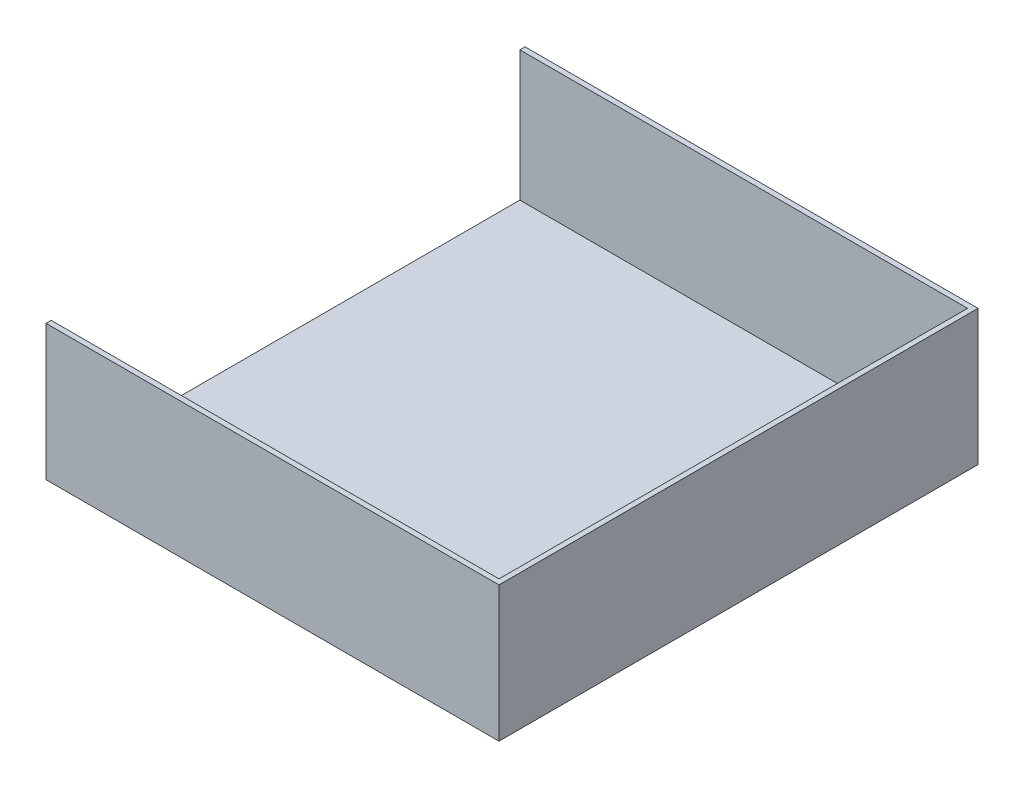
SolidWorks part; units mm, degrees
ref_plane "Front Plane" through (0, 0, 0) normal (0, 0, 1) x (1, 0, 0)
ref_plane "Top Plane" through (0, 0, 0) normal (0, 1, 0) x (1, 0, 0)
ref_plane "Right Plane" through (0, 0, 0) normal (1, 0, 0) x (0, 0, -1)
sketch "Sketch1" plane through (0, 0, 0) normal (0, 1, 0) x (1, 0, 0)
  line L1 (0, 0) -> (279.4, 0)
  line L2 (0, 0) -> (0, 292.1)
  line L3 (0, 292.1) -> (279.4, 292.1)
  line L4 (279.4, 0) -> (279.4, 292.1)
  dimension "D1" = 279.4
  dimension "D2" = 292.1
extrude "Boss-Extrude1" add sketch "Sketch1" along normal blind 82.55
sketch "Sketch3" plane through (0, 82.55, 0) normal (0, 1, 0) x (1, 0, 0)
  line L14 (3.175, 3.175) -> (276.225, 3.175)
  line L15 (276.225, 3.175) -> (276.225, 288.925)
  line L16 (3.175, 288.925) -> (3.175, 3.175)
  line L17 (276.225, 288.925) -> (3.175, 288.925)
  line L18 (3.175, 3.175) -> (276.225, 3.175)
  line L19 (276.225, 3.175) -> (276.225, 288.925)
  line L20 (3.175, 288.925) -> (3.175, 3.175)
  line L21 (276.225, 288.925) -> (3.175, 288.925)
  dimension "D1" = 3.175
extrude "Cut-Extrude1" cut sketch "Sketch3" against normal blind 79.375
sketch "Sketch4" plane through (0, 82.55, 0) normal (0, 1, 0) x (1, 0, 0)
  line L0 (279.4, 292.1) -> (0, 292.1) construction
  line L6 (3.175, 288.925) -> (3.175, 3.175) construction
  line L7 (0, 0) -> (3.175, 0)
  line L8 (0, 0) -> (0, 292.1)
  line L9 (0, 292.1) -> (3.175, 292.1)
  line L10 (3.175, 0) -> (3.175, 292.1)
extrude "Cut-Extrude2" cut sketch "Sketch4" against normal up to next
